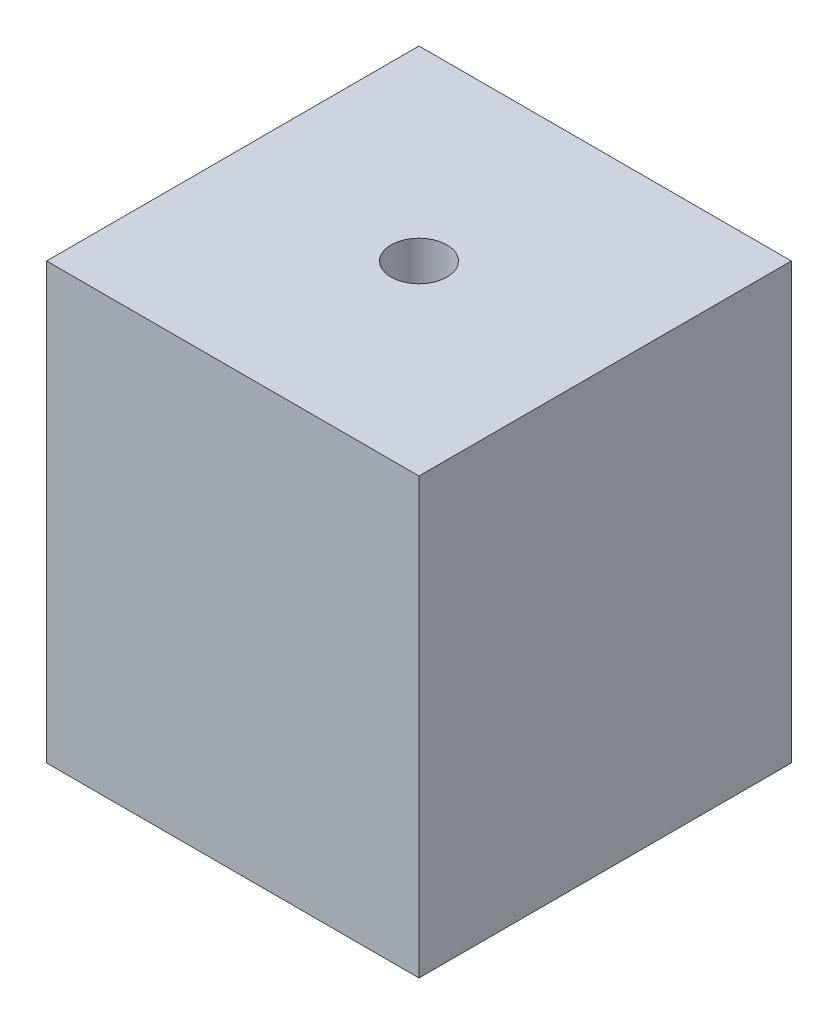
SolidWorks part; units mm, degrees
ref_plane "前视基准面" through (0, 0, 0) normal (0, 0, 1) x (1, 0, 0)
ref_plane "上视基准面" through (0, 0, 0) normal (0, 1, 0) x (1, 0, 0)
ref_plane "右视基准面" through (0, 0, 0) normal (1, 0, 0) x (0, 0, -1)
other "Configuration Table"
sketch "草图1" plane through (0, 0, 0) normal (0, 1, 0) x (1, 0, 0)
  line L1 (-10, 10) -> (10, 10)
  line L2 (-10, 10) -> (-10, -10)
  line L3 (-10, -10) -> (10, -10)
  line L4 (10, 10) -> (10, -10)
  line L5 (-10, 10) -> (10, -10) construction
  line L6 (-10, -10) -> (10, 10) construction
  point P0 (0, 0)
  dimension "D1" = 20
  dimension "D2" = 20
extrude "凸台-拉伸1" add sketch "草图1" along normal blind 23.35
sketch "草图3" plane through (0, 23.35, 0) normal (0, 1, 0) x (1, 0, 0)
  circle A0 centre (0, 0) radius 1.5
  dimension "D1" = 3
extrude "切除-拉伸1" cut sketch "草图3" against normal through all both and the other way through all
